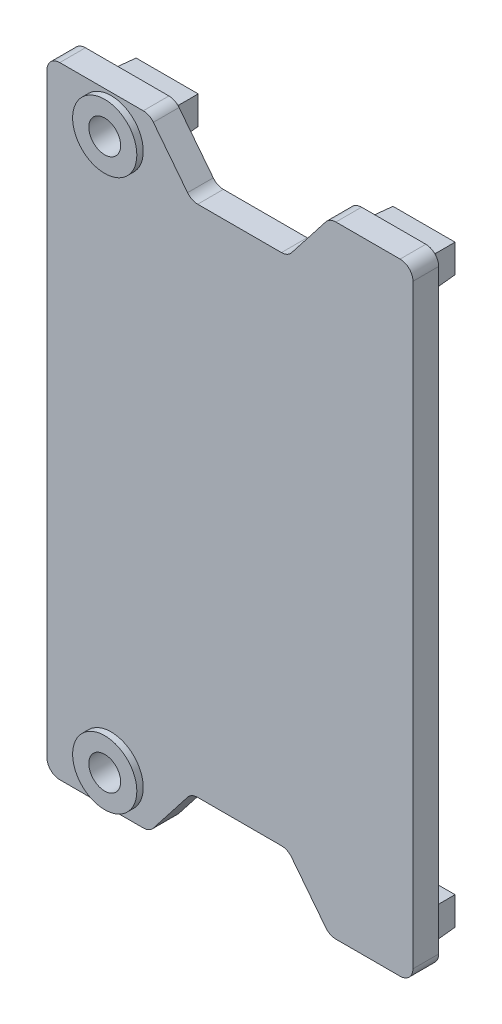
SolidWorks part; units mm, degrees
ref_plane "Front Plane" through (0, 0, 0) normal (0, 0, 1) x (1, 0, 0)
ref_plane "Top Plane" through (0, 0, 0) normal (0, 1, 0) x (1, 0, 0)
ref_plane "Right Plane" through (0, 0, 0) normal (1, 0, 0) x (0, 0, -1)
sketch "Sketch1" plane through (0, 0, 0) normal (0, 0, 1) x (1, 0, 0)
  line L0 (190.5, 25.4) -> (-190.5, -25.4) construction
  line L1 (190.5, -38.1) -> (-190.5, -38.1) construction
  line L2 (190.5, -38.1) -> (190.5, 38.1) construction
  line L3 (190.5, 38.1) -> (-190.5, 38.1) construction
  line L4 (-190.5, -38.1) -> (-190.5, 38.1) construction
  line L5 (190.5, -38.1) -> (-190.5, 38.1) construction
  line L6 (190.5, 38.1) -> (-190.5, -38.1) construction
  line L7 (-190.5, 32.79) -> (190.5, 32.79) construction
  line L8 (-184.15, 30.71) -> (-180.975, 30.71)
  line L9 (190.5, 25.4) -> (-190.5, 25.4) construction
  line L10 (-179.9737, 30.2212) -> (-176.5938, 25.8888)
  line L11 (-166.3062, 25.8888) -> (-162.9263, 30.2212)
  line L12 (-161.925, 30.71) -> (-155.575, 30.71)
  line L13 (-154.305, 29.44) -> (-154.305, 0)
  line L14 (0, 0) -> (-190.5, 0) construction
  line L15 (-154.305, 0) -> (-190.5, 0)
  line L16 (-190.5, 0) -> (-190.5, 25.4)
  line L17 (-175.5925, 25.4) -> (-167.3075, 25.4)
  line L18 (-184.15, 30.71) -> (-189.23, 30.71)
  line L19 (-155.575, 29.44) -> (-161.925, 29.44) construction
  line L20 (-155.575, 29.44) -> (-155.575, 26.44) construction
  line L21 (-155.575, 26.44) -> (-161.925, 26.44) construction
  line L22 (-161.925, 29.44) -> (-161.925, 26.44) construction
  line L23 (-155.575, 29.44) -> (-161.925, 26.44) construction
  line L24 (-155.575, 26.44) -> (-161.925, 29.44) construction
  line L25 (-190.5, 25.4) -> (-190.5, 29.44)
  line L27 (-180.975, 29.44) -> (-187.325, 29.44) construction
  line L28 (-180.975, 29.44) -> (-180.975, 26.44) construction
  line L29 (-180.975, 26.44) -> (-187.325, 26.44) construction
  line L30 (-187.325, 29.44) -> (-187.325, 26.44) construction
  line L31 (-180.975, 29.44) -> (-187.325, 26.44) construction
  line L32 (-180.975, 26.44) -> (-187.325, 29.44) construction
  circle A0 centre (-184.15, 27.2465) radius 5.5436 construction
  circle A1 centre (-184.15, 27.2465) radius 4.5 construction
  circle A2 centre (-184.15, 27.2465) radius 1.575
  circle A3 centre (-184.15, 27.2465) radius 3.175 construction
  arc A4 (-175.5925, 25.4) -> (-176.5938, 25.8888) centre (-175.5925, 26.67) cw
  arc A5 (-167.3075, 25.4) -> (-166.3062, 25.8888) centre (-167.3075, 26.67) ccw
  arc A6 (-162.9263, 30.2212) -> (-161.925, 30.71) centre (-161.925, 29.44) cw
  arc A7 (-154.305, 29.44) -> (-155.575, 30.71) centre (-155.575, 29.44) ccw
  arc A8 (-179.9737, 30.2212) -> (-180.975, 30.71) centre (-180.975, 29.44) ccw
  arc A9 (-189.23, 30.71) -> (-190.5, 29.44) centre (-189.23, 29.44) ccw
  point P0 (0, 0)
  point P27 (-158.75, 27.94)
  point P37 (-176.2125, 25.4)
  point P40 (-166.6875, 25.4)
  point P46 (-176.2125, 25.4)
  point P51 (-190.5, 30.71)
  point P54 (-184.15, 27.94)
  dimension "D3" = 9
  dimension "D4" = 11.0871
  dimension "D6" = 3.15
  dimension "D7" = 6.35
  dimension "D14" = 1.27
  dimension "D1" = 76.2
  dimension "D2" = 5.31
  dimension "D5" = 6.35
  dimension "D8" = 9.525
  dimension "D9" = 14.2875
  dimension "D10" = 3
  dimension "D11" = 6.35
  dimension "D12" = 27.94
  dimension "D13" = 31.75
  dimension "D15" = 6.35
  dimension "D16" = 6.35
  dimension "D17" = 3
extrude "Boss-Extrude1" add sketch "Sketch1" along normal blind 2.54
sketch "Sketch2" plane through (0, 0, 2.54) normal (0, 0, 1) x (1, 0, 0)
  circle A0 centre (-184.15, 27.2465) radius 1.575
  circle A1 centre (-184.15, 27.2465) radius 3.175
  circle A2 centre (-184.15, 27.2465) radius 1.575 construction
  dimension "D1" = 6.35
extrude "Boss-Extrude2" add sketch "Sketch2" along normal offset from surface (0.635 mm away) 3.175 up to face at (-171.8582, 24.6619, 0)
sketch "Sketch3" plane through (0, 0, 0) normal (0, 0, -1) x (-1, 0, 0)
  line L0 (0, 0) -> (197.0263, 0) construction
  line L1 (187.325, 26.44) -> (180.975, 26.44)
  line L2 (187.325, 26.44) -> (187.325, 29.44)
  line L3 (187.325, 29.44) -> (180.975, 29.44)
  line L4 (180.975, 26.44) -> (180.975, 29.44)
  line L5 (187.325, 26.44) -> (180.975, 29.44) construction
  line L6 (187.325, 29.44) -> (180.975, 26.44) construction
  line L7 (161.925, 26.44) -> (155.575, 26.44)
  line L8 (161.925, 26.44) -> (161.925, 29.44)
  line L9 (161.925, 29.44) -> (155.575, 29.44)
  line L10 (155.575, 26.44) -> (155.575, 29.44)
  line L11 (161.925, 26.44) -> (155.575, 29.44) construction
  line L12 (161.925, 29.44) -> (155.575, 26.44) construction
  line L13 (-190.5, 25.4) -> (190.5, -25.4) construction
  point P0 (184.15, 27.94)
  point P5 (158.75, 27.94)
  dimension "D1" = 6.35
  dimension "D2" = 3
  dimension "D3" = 27.94
  dimension "D4" = 25.4
  dimension "D5" = 6.35
extrude "Boss-Extrude3" add sketch "Sketch3" along normal blind 1
sketch "Sketch4" plane through (0, 0, -1) normal (0, 0, -1) x (-1, 0, 0)
  line L0 (180.975, 29.44) -> (180.975, 26.44) construction
  line L1 (180.975, 26.44) -> (187.325, 26.44) construction
  line L2 (187.325, 26.44) -> (187.325, 29.44) construction
  line L3 (187.325, 29.44) -> (180.975, 29.44) construction
  line L4 (155.575, 29.44) -> (155.575, 26.44) construction
  line L5 (155.575, 26.44) -> (161.925, 26.44) construction
  line L6 (161.925, 26.44) -> (161.925, 29.44) construction
  line L7 (161.925, 29.44) -> (155.575, 29.44) construction
  line L8 (180.975, 29.44) -> (180.975, 26.44)
  line L9 (180.975, 26.44) -> (187.325, 26.44)
  line L10 (187.325, 26.44) -> (187.325, 29.44)
  line L11 (187.325, 29.44) -> (180.975, 29.44)
  line L12 (155.575, 29.44) -> (155.575, 26.44)
  line L13 (155.575, 26.44) -> (161.925, 26.44)
  line L14 (161.925, 26.44) -> (161.925, 29.44)
  line L15 (161.925, 29.44) -> (155.575, 29.44)
extrude "Boss-Extrude4" add sketch "Sketch4" along normal offset from surface 3 draft 3
mirror "Mirror1" about plane through (0, 0, 0) normal (0, 1, 0) of bodies 105 102
